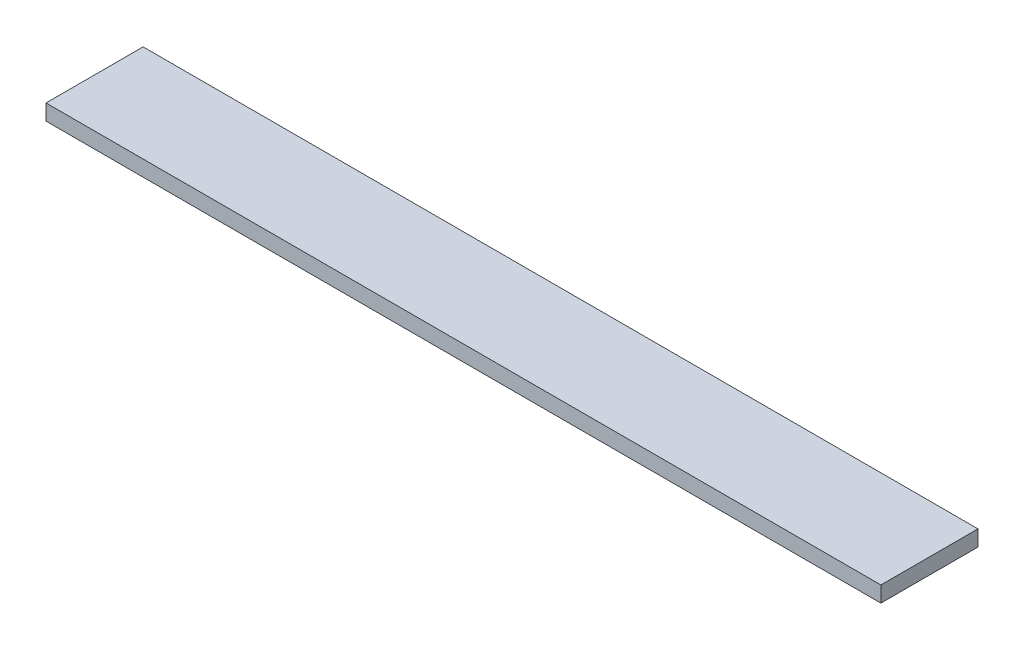
SolidWorks part; units mm, degrees
material "Pine"
ref_plane "Front Plane" through (0, 0, 0) normal (0, 0, 1) x (1, 0, 0)
ref_plane "Top Plane" through (0, 0, 0) normal (0, 1, 0) x (1, 0, 0)
ref_plane "Right Plane" through (0, 0, 0) normal (1, 0, 0) x (0, 0, -1)
sketch "Sketch2" plane through (0, 0, 0) normal (0, 1, 0) x (1, 0, 0)
  line L1 (-11516.3203, 5174.4563) -> (-9497.0203, 5174.4563)
  line L2 (-11516.3203, 5174.4563) -> (-11516.3203, 4939.5063)
  line L3 (-11516.3203, 4939.5063) -> (-9497.0203, 4939.5063)
  line L4 (-9497.0203, 5174.4563) -> (-9497.0203, 4939.5063)
  dimension "D1" = 2019.3
  dimension "D2" = 234.95
extrude "Boss-Extrude1" add sketch "Sketch2" along normal blind 38.1
